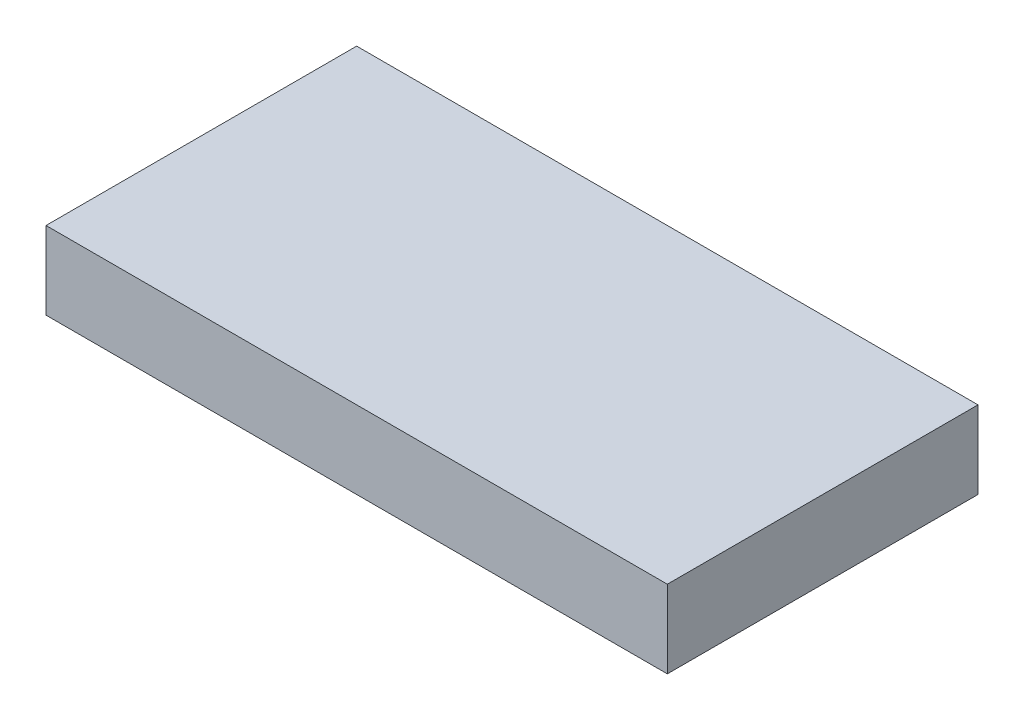
SolidWorks part; units mm, degrees
ref_plane "Front Plane" through (0, 0, 0) normal (0, 0, 1) x (1, 0, 0)
ref_plane "Top Plane" through (0, 0, 0) normal (0, 1, 0) x (1, 0, 0)
ref_plane "Right Plane" through (0, 0, 0) normal (1, 0, 0) x (0, 0, -1)
sketch "Sketch1" plane through (0, 0, 0) normal (0, 1, 0) x (1, 0, 0)
  line L1 (-25.4, 12.7) -> (25.4, 12.7)
  line L2 (-25.4, 12.7) -> (-25.4, -12.7)
  line L3 (-25.4, -12.7) -> (25.4, -12.7)
  line L4 (25.4, 12.7) -> (25.4, -12.7)
  line L5 (-25.4, 12.7) -> (25.4, -12.7) construction
  line L6 (-25.4, -12.7) -> (25.4, 12.7) construction
  point P0 (0, 0)
  dimension "D1" = 25.4
  dimension "D2" = 50.8
extrude "Boss-Extrude1" add sketch "Sketch1" along normal blind 6.35
